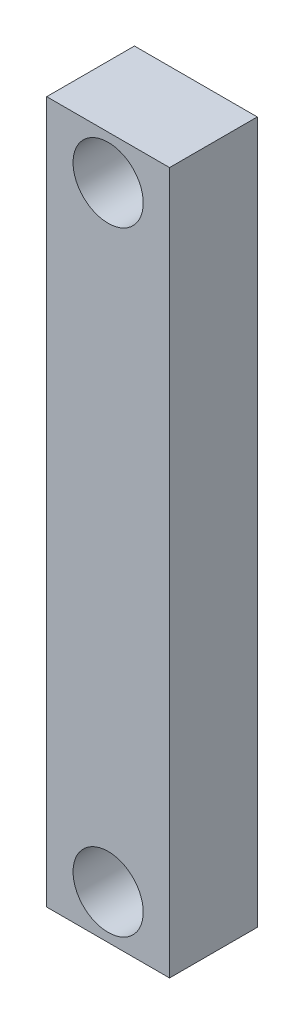
SolidWorks part; units mm, degrees
ref_plane "Front Plane" through (0, 0, 0) normal (0, 0, 1) x (1, 0, 0)
ref_plane "Top Plane" through (0, 0, 0) normal (0, 1, 0) x (1, 0, 0)
ref_plane "Right Plane" through (0, 0, 0) normal (1, 0, 0) x (0, 0, -1)
sketch "Sketch1" plane through (0, 0, 0) normal (0, 0, 1) x (1, 0, 0)
  line L1 (-3.5, 20) -> (3.5, 20)
  line L2 (-3.5, 20) -> (-3.5, -20)
  line L3 (-3.5, -20) -> (3.5, -20)
  line L4 (3.5, 20) -> (3.5, -20)
  line L5 (-3.5, 20) -> (3.5, -20) construction
  line L6 (-3.5, -20) -> (3.5, 20) construction
  circle A0 centre (0, 17.5) radius 2
  circle A1 centre (0, -17.5) radius 2
  point P0 (0, 0)
  point P9 (0, 17.5)
  dimension "D5" = 4
  dimension "D1" = 7
  dimension "D2" = 40
  dimension "D3" = 35
  dimension "D4" = 2.5
extrude "Boss-Extrude1" add sketch "Sketch1" along normal blind 5
sketch "Sketch2" plane through (0, 0, 5) normal (0, 0, 1) x (1, 0, 0)
  circle A2 centre (0, -17.5) radius 2
  point P0 (0, -17.5)
  dimension "D1" = 4
sketch "Sketch3" plane through (0, 0, 0) normal (0, 0, -1) x (-1, 0, 0)
  circle A0 centre (0, -17.5) radius 2.25
  point P3 (0, -17.5)
  dimension "D1" = 4.5
extrude "Boss-Extrude2" add sketch "Sketch3" against normal blind 2 contours A0
sketch "Sketch4" plane through (0, 0, 2) normal (0, 0, 1) x (1, 0, 0)
  circle A0 centre (0, -17.5) radius 1.5
  dimension "D1" = 3
extrude "Cut-Extrude1" cut sketch "Sketch4" against normal blind 2
